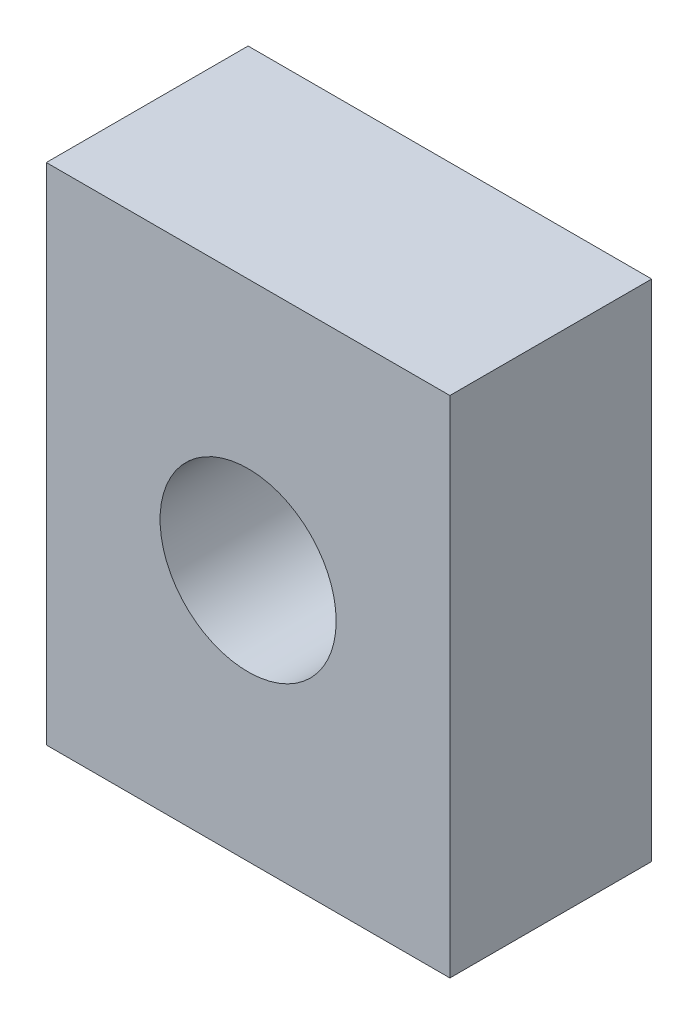
SolidWorks part; units mm, degrees
material "Cast Alloy Steel"
ref_plane "Front Plane" through (0, 0, 0) normal (0, 0, 1) x (1, 0, 0)
ref_plane "Top Plane" through (0, 0, 0) normal (0, 1, 0) x (1, 0, 0)
ref_plane "Right Plane" through (0, 0, 0) normal (1, 0, 0) x (0, 0, -1)
sketch "BlockBase" plane through (0, 0, 0) normal (0, 0, 1) x (1, 0, 0)
  line L1 (-50.8, -63.5) -> (50.8, -63.5)
  line L2 (-50.8, -63.5) -> (-50.8, 63.5)
  line L3 (-50.8, 63.5) -> (50.8, 63.5)
  line L4 (50.8, -63.5) -> (50.8, 63.5)
  line L5 (-50.8, -63.5) -> (50.8, 63.5) construction
  line L6 (-50.8, 63.5) -> (50.8, -63.5) construction
  point P0 (0, 0)
  dimension "Length" = 101.6
  dimension "Width" = 127
extrude "Block" add sketch "BlockBase" along normal blind 50.8
sketch "Sketch1" plane through (0, 0, 50.8) normal (0, 0, 1) x (1, 0, 0)
  circle A0 centre (0, 0) radius 22.1659
extrude "Cut-Extrude1" cut sketch "Sketch1" against normal through all
